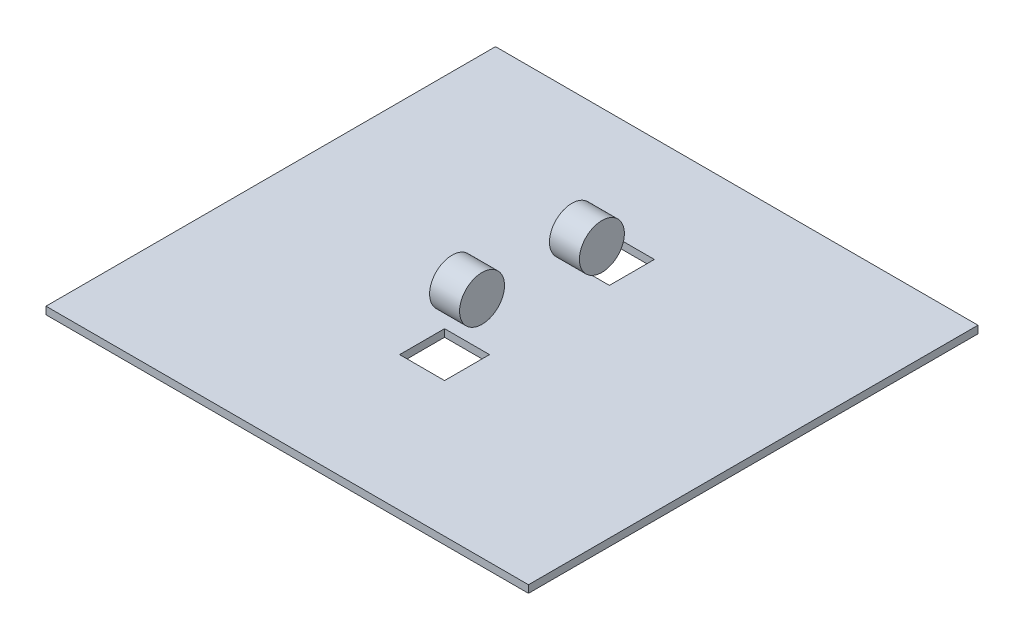
SolidWorks part; units mm, degrees
ref_plane "정면" through (0, 0, 0) normal (0, 0, 1) x (1, 0, 0)
ref_plane "윗면" through (0, 0, 0) normal (0, 1, 0) x (1, 0, 0)
ref_plane "우측면" through (0, 0, 0) normal (1, 0, 0) x (0, 0, -1)
sketch "스케치1" plane through (0, 0, 0) normal (0, 1, 0) x (1, 0, 0)
  line L1 (0, 0) -> (322, 0)
  line L2 (0, 0) -> (0, 300)
  line L3 (0, 300) -> (322, 300)
  line L4 (322, 0) -> (322, 300)
  dimension "D1" = 322
  dimension "D2" = 300
extrude "보스-돌출1" add sketch "스케치1" along normal blind 5
sketch "스케치2" plane through (0, 5, 0) normal (0, 1, 0) x (1, 0, 0)
  line L0 (161, 300) -> (161, 0) construction
  line L1 (146, 90) -> (176, 90)
  line L2 (146, 90) -> (146, 120)
  line L3 (146, 120) -> (176, 120)
  line L4 (176, 90) -> (176, 120)
  line L5 (146, 200) -> (176, 200)
  line L6 (146, 200) -> (146, 230)
  line L7 (146, 230) -> (176, 230)
  line L8 (176, 200) -> (176, 230)
  line L9 (0, 0) -> (322, 0) construction
  point P9 (200.9971, 199.4879)
  point P12 (161, 0)
  point P13 (161, 230)
  point P15 (161, 120)
  dimension "D1" = 30
  dimension "D2" = 30
  dimension "D3" = 30
  dimension "D4" = 30
  dimension "D5" = 90
  dimension "D6" = 80
extrude "컷-돌출1" cut sketch "스케치2" against normal blind 5
sketch "스케치3" plane through (0, 0, 0) normal (0, -1, 0) x (1, 0, 0)
  line L0 (322, -105) -> (0, -105)
  line L1 (322, 0) -> (322, -300) construction
  line L2 (0, -300) -> (0, 0) construction
  line L3 (176, -90) -> (176, -120) construction
  circle A0 centre (252, -105) radius 7.5
  circle A1 centre (70, -105) radius 7.5
  point P8 (176, -105)
  point P13 (0, 0)
  dimension "D1" = 15
  dimension "D2" = 15
  dimension "D3" = 70
  dimension "D4" = 70
extrude "컷-돌출2" cut sketch "스케치3" against normal blind 2 contours L0 A1 | L0 A1 | L0 A0 | L0 A0
sketch "스케치4" plane through (0, 0, 0) normal (0, -1, 0) x (1, 0, 0)
  line L0 (0, -215) -> (322, -215)
  line L1 (0, -300) -> (0, 0) construction
  line L2 (322, 0) -> (322, -300) construction
  line L3 (176, -200) -> (176, -230) construction
  circle A0 centre (202, -215) radius 7.5
  circle A1 centre (120, -215) radius 7.5
  point P8 (176, -215)
  point P9 (120, -215)
  point P10 (202, -215)
  dimension "D3" = 15
  dimension "D4" = 15
  dimension "D1" = 120
  dimension "D2" = 120
extrude "컷-돌출3" cut sketch "스케치4" against normal blind 2 contours L0 A0 | L0 A0 | L0 A1 | L0 A1
ref_plane "평면1" through (161, 0, 0) normal (1, 0, 0) x (0, 0, -1)
sketch "스케치5" plane through (161, 0, 0) normal (1, 0, 0) x (0, 0, -1)
  line L3 (90, 5) -> (120, 5) construction
  line L4 (200, 5) -> (230, 5) construction
  circle A0 centre (120, 35) radius 15
  circle A1 centre (200, 25) radius 15
  point P4 (121.0303, 21.2668)
  point P5 (206.727, 21.2668)
  point P7 (0, 0)
  point P9 (105, 5)
  point P12 (215, 5)
  dimension "D1" = 30
  dimension "D2" = 30
  dimension "D3" = 15
  dimension "D4" = 15
  dimension "D5" = 30
  dimension "D6" = 20
extrude "보스-돌출3" add sketch "스케치5" along normal mid plane 20 separate body
